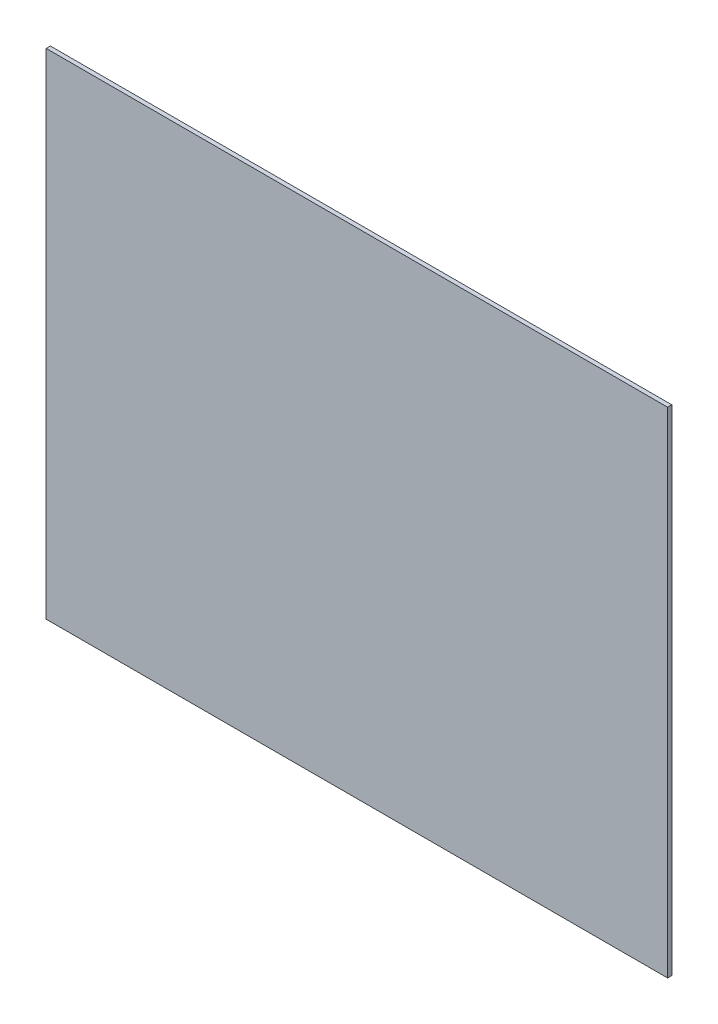
SolidWorks part; units mm, degrees
ref_plane "Front Plane" through (0, 0, 0) normal (0, 0, 1) x (1, 0, 0)
ref_plane "Top Plane" through (0, 0, 0) normal (0, 1, 0) x (1, 0, 0)
ref_plane "Right Plane" through (0, 0, 0) normal (1, 0, 0) x (0, 0, -1)
sketch "Sketch1" plane through (0, 0, 0) normal (0, 0, 1) x (1, 0, 0)
  line L1 (0, 104) -> (445, 104)
  line L2 (0, 104) -> (0, -250)
  line L3 (0, -250) -> (445, -250)
  line L4 (445, 104) -> (445, -250)
extrude "Boss-Extrude1" add sketch "Sketch1" along normal blind 3 contours L2 L3 L4 L1
